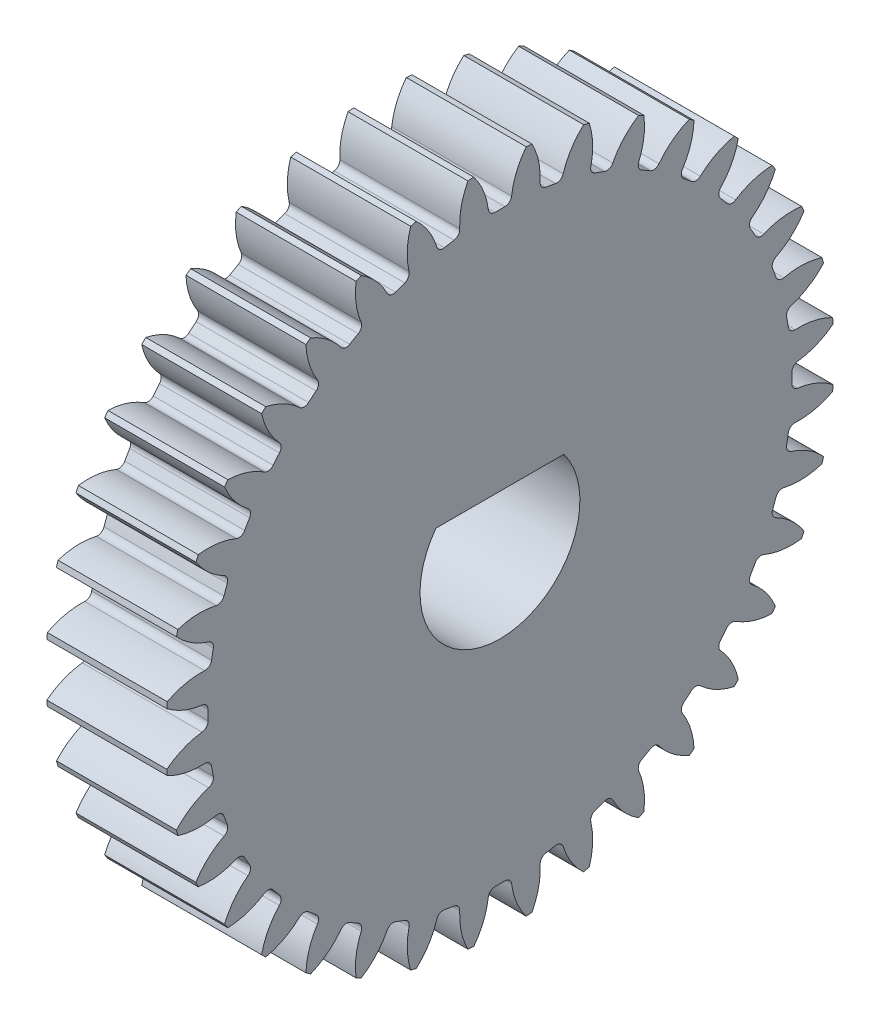
SolidWorks part; units mm, degrees
ref_plane "Front Plane" through (0, 0, 0) normal (0, 0, 1) x (1, 0, 0)
ref_plane "Top Plane" through (0, 0, 0) normal (0, 1, 0) x (1, 0, 0)
ref_plane "Right Plane" through (0, 0, 0) normal (1, 0, 0) x (0, 0, -1)
sketch "Sketch1" plane through (0, 0, 0) normal (1, 0, 0) x (0, 0, -1)
  circle A0 centre (0, 0) radius 5
  circle A1 centre (0, 0) radius 20.9
  dimension "D1" = 10
  dimension "D2" = 41.8
extrude "Boss-Extrude2" add sketch "Sketch1" along normal blind 7.5
sketch "Sketch3" plane through (7.5, 0, 0) normal (1, 0, 0) x (0, 0, -1)
  line L0 (0, 0) -> (0, 20.9) construction
  line L1 (-0.6995, 18.2466) -> (0, 0) construction
  line L2 (0, 16.9556) -> (-1.7175, 21.6745) construction
  circle A0 centre (0, 0) radius 20.9 construction
  arc A1 (0.6995, 18.2466) -> (-0.6995, 18.2466) centre (0, 0) ccw
  arc A2 (1.0289, 19.7732) -> (-1.0289, 19.7732) centre (0, 0) ccw construction
  arc A3 (1.6417, 20.8354) -> (-1.6417, 20.8354) centre (0, 0) ccw
  arc A4 (-1.6417, 20.8354) -> (-0.6995, 18.2466) centre (-5.2011, 18.074) cw
  arc A5 (1.6417, 20.8354) -> (0.6995, 18.2466) centre (5.2011, 18.074) ccw
  point P17 (-0.9679, 19.6148)
  dimension "D1" = 41.8
  dimension "D2" = 39.6
  dimension "D3" = 2.64
  dimension "D4" = 20
  dimension "D5" = 2.0579
extrude "Cut-Extrude1" cut sketch "Sketch3" against normal through all
fillet "Fillet1" radius 0.418 2 edges at (3.75, 18.2466, -0.6995) (3.75, 18.2466, 0.6995)
pattern_circular "CirPattern2" count 36 over 360 about axis through (0, 0, 0) along (1, 0, 0) of "Fillet1", "Cut-Extrude1"
sketch "Sketch4" plane through (7.5, 0, 0) normal (1, 0, 0) x (0, 0, -1)
  line L0 (-4, 3) -> (4, 3)
  circle A0 centre (0, 0) radius 5 construction
  arc A1 (-4, 3) -> (4, 3) centre (0, 0) cw
  dimension "D1" = 3
extrude "Boss-Extrude3" add sketch "Sketch4" against normal up to surface (7.5 mm away) up to face at (0, 0, -5)
equation "\"No of teeth\"= 36"
equation "\"Module\"= 1.1"
equation "\"Outer Diameter\"= ( \"No of teeth\" + 2 ) * \"Module\""
equation "\"Pitch Diameter\"= \"No of teeth\" * \"Module\""
equation "\"Backlash\"= 0.3 * \"Module\""
equation "\"Arc Length\"= ( ( \"Module\" * pi ) / 2 ) + \"Backlash\""
equation "\"Fillet Radius\"= 0.38 * \"Module\""
equation "\"Bore Diameter\"=10"
equation "\"Presseure angle\"= 20"
equation "\"Tooth Depth\"= IIF ( \"Module\" <= 1.25 , 2.4 * \"Module\" , 2.25 * \"Module\" )"
equation "\"D1@Sketch1\"=\"Bore Diameter\""
equation "\"D2@Sketch1\"=\"Outer Diameter\""
equation "\"D1@Sketch3\"=\"Outer Diameter\""
equation "\"D2@Sketch3\"=\"Pitch Diameter\""
equation "\"D3@Sketch3\"=\"Tooth Depth\""
equation "\"D4@Sketch3\"=\"Presseure angle\""
equation "\"D5@Sketch3\"=\"Arc Length\""
equation "\"D1@Fillet1\"=\"Fillet Radius\""
equation "\"D1@CirPattern2\"=\"No of teeth\""
